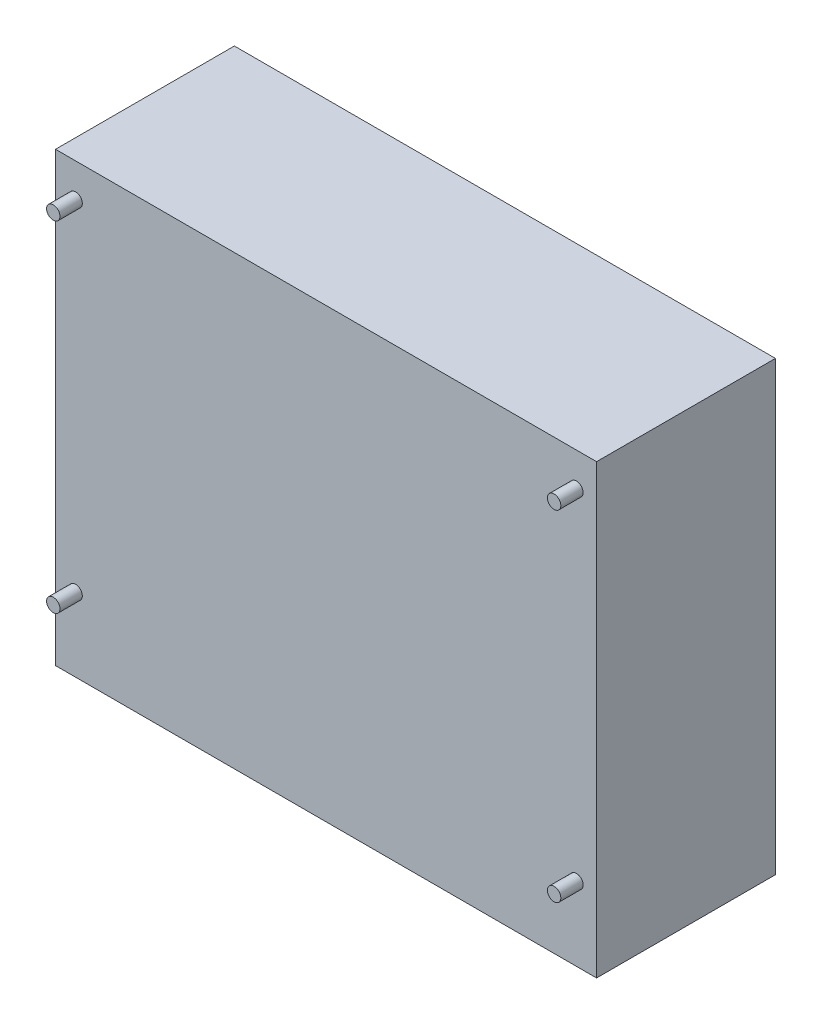
SolidWorks part; units mm, degrees
ref_plane "前视基准面" through (0, 0, 0) normal (0, 0, 1) x (1, 0, 0)
ref_plane "上视基准面" through (0, 0, 0) normal (0, 1, 0) x (1, 0, 0)
ref_plane "右视基准面" through (0, 0, 0) normal (1, 0, 0) x (0, 0, -1)
other "Configuration Table"
sketch "草图1" plane through (0, 0, 0) normal (0, 0, 1) x (1, 0, 0)
  line L1 (0, 0) -> (-121, 0)
  line L2 (0, 0) -> (0, 100)
  line L3 (0, 100) -> (-121, 100)
  line L4 (-121, 0) -> (-121, 100)
  dimension "D1" = 121
  dimension "D2" = 100
extrude "凸台-拉伸1" add sketch "草图1" along normal blind 40
sketch "草图2" plane through (0, 0, 40) normal (0, 0, 1) x (1, 0, 0)
  line L0 (0, 100) -> (-121, 100) construction
  line L1 (-116.5, 92.5) -> (-4.5, 92.5) construction
  line L2 (-116.5, 92.5) -> (-116.5, 16.5) construction
  line L3 (-116.5, 16.5) -> (-4.5, 16.5) construction
  line L4 (-4.5, 92.5) -> (-4.5, 16.5) construction
  line L5 (-121, 100) -> (-121, 0) construction
  circle A0 centre (-116.5, 92.5) radius 1.5
  circle A1 centre (-4.5, 92.5) radius 1.5
  circle A2 centre (-116.5, 16.5) radius 1.5
  circle A3 centre (-4.5, 16.5) radius 1.5
  dimension "D5" = 3
  dimension "D6" = 3
  dimension "D7" = 3
  dimension "D8" = 3
  dimension "D1" = 112
  dimension "D2" = 76
  dimension "D3" = 7.5
  dimension "D4" = 4.5
extrude "凸台-拉伸2" add sketch "草图2" along normal blind 5
sketch "草图3" plane through (0, 0, 0) normal (0, 0, -1) x (-1, 0, 0)
  line L0 (0, 50) -> (121, 50) construction
  line L1 (0, 0) -> (0, 100) construction
  line L2 (121, 100) -> (121, 0) construction
  line L3 (60.5, 100) -> (60.5, 0) construction
  line L4 (0, 100) -> (121, 100) construction
  line L5 (121, 0) -> (0, 0) construction
  line L7 (119, 2) -> (2, 2)
  line L8 (119, 2) -> (119, 98)
  line L9 (119, 98) -> (2, 98)
  line L10 (2, 2) -> (2, 98)
  line L11 (119, 2) -> (2, 98) construction
  line L12 (119, 98) -> (2, 2) construction
  point P12 (60.5, 50)
  dimension "D1" = 2
  dimension "D2" = 2
extrude "切除-拉伸1" cut sketch "草图3" against normal offset from surface (38 mm away) 2 up to face at (-3, 16.5, 40)
sketch "草图4" plane through (0, 0, 0) normal (0, 0, -1) x (-1, 0, 0)
  line L1 (2, 2) -> (119, 2)
  line L2 (2, 2) -> (2, 98)
  line L3 (2, 98) -> (119, 98)
  line L4 (119, 2) -> (119, 98)
extrude "凸台-拉伸3" add sketch "草图4" against normal blind 2
